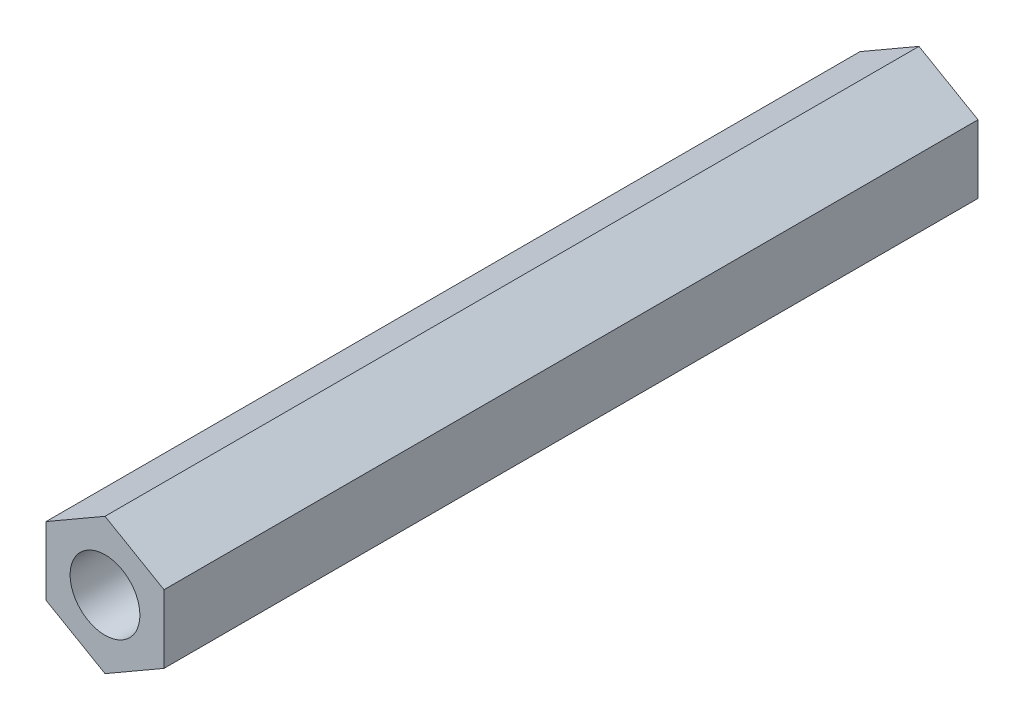
SolidWorks part; units mm, degrees
ref_plane "Plan de face" through (0, 0, 0) normal (0, 0, 1) x (1, 0, 0)
ref_plane "Plan de dessus" through (0, 0, 0) normal (0, 1, 0) x (1, 0, 0)
ref_plane "Plan de droite" through (0, 0, 0) normal (1, 0, 0) x (0, 0, -1)
sketch "Esquisse1" plane through (0, 0, 0) normal (0, 0, 1) x (1, 0, 0)
  line L1 (2.5375, -1.465) -> (2.5375, 1.465)
  line L2 (2.5375, 1.465) -> (0, 2.93)
  line L3 (0, 2.93) -> (-2.5375, 1.465)
  line L4 (-2.5375, 1.465) -> (-2.5375, -1.465)
  line L5 (-2.5375, -1.465) -> (0, -2.93)
  line L6 (0, -2.93) -> (2.5375, -1.465)
  circle A0 centre (0, 0) radius 2.5375 construction
  circle A1 centre (0, 0) radius 1.5
  dimension "D2" = 3
  dimension "D1" = 5.86
extrude "Boss.-Extru.1" add sketch "Esquisse1" along normal blind 35
